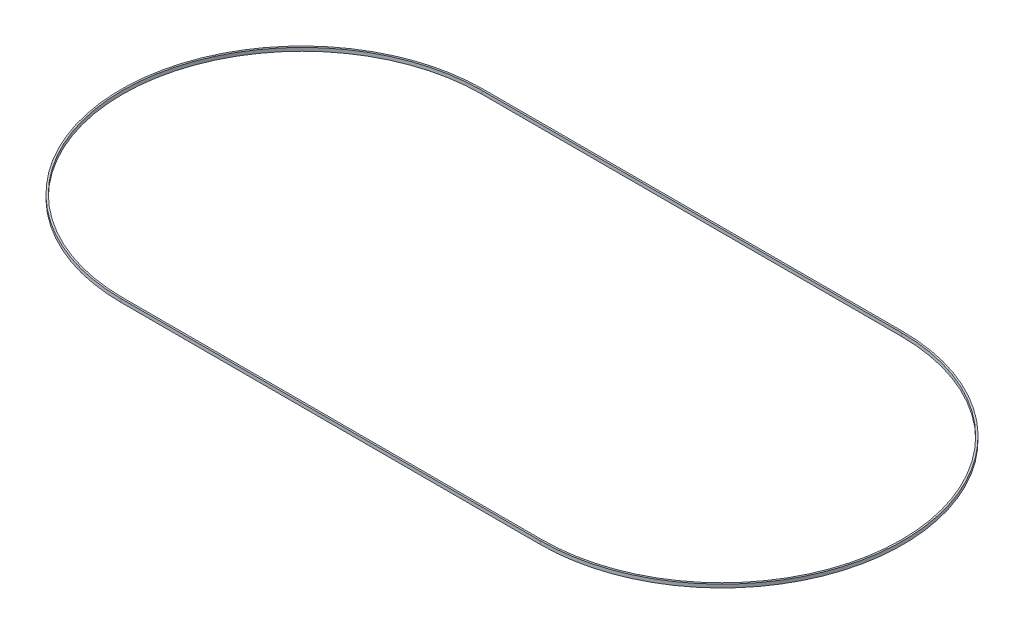
SolidWorks part; units mm, degrees
ref_plane "Front Plane" through (0, 0, 0) normal (0, 0, 1) x (1, 0, 0)
ref_plane "Top Plane" through (0, 0, 0) normal (0, 1, 0) x (1, 0, 0)
ref_plane "Right Plane" through (0, 0, 0) normal (1, 0, 0) x (0, 0, -1)
sketch "Sketch1" plane through (0, 0, 0) normal (0, 1, 0) x (1, 0, 0)
  line L6 (-25000, -21400) -> (25000, -21400)
  line L7 (-25000, 21400) -> (25000, 21400)
  line L8 (-25000, -21600) -> (25000, -21600)
  line L9 (-25000, 21600) -> (25000, 21600)
  arc A4 (25000, 21400) -> (25000, -21400) centre (25000, 0) cw
  arc A5 (-25000, 21400) -> (-25000, -21400) centre (-25000, 0) ccw
  arc A6 (25000, 21600) -> (25000, -21600) centre (25000, 0) cw
  arc A7 (-25000, 21600) -> (-25000, -21600) centre (-25000, 0) ccw
  dimension "D7" = 200
extrude "Boss-Extrude2" add sketch "Sketch1" along normal blind 400 separate body contours A5 L6 A4 L7 | A7 L8 A6 L9
